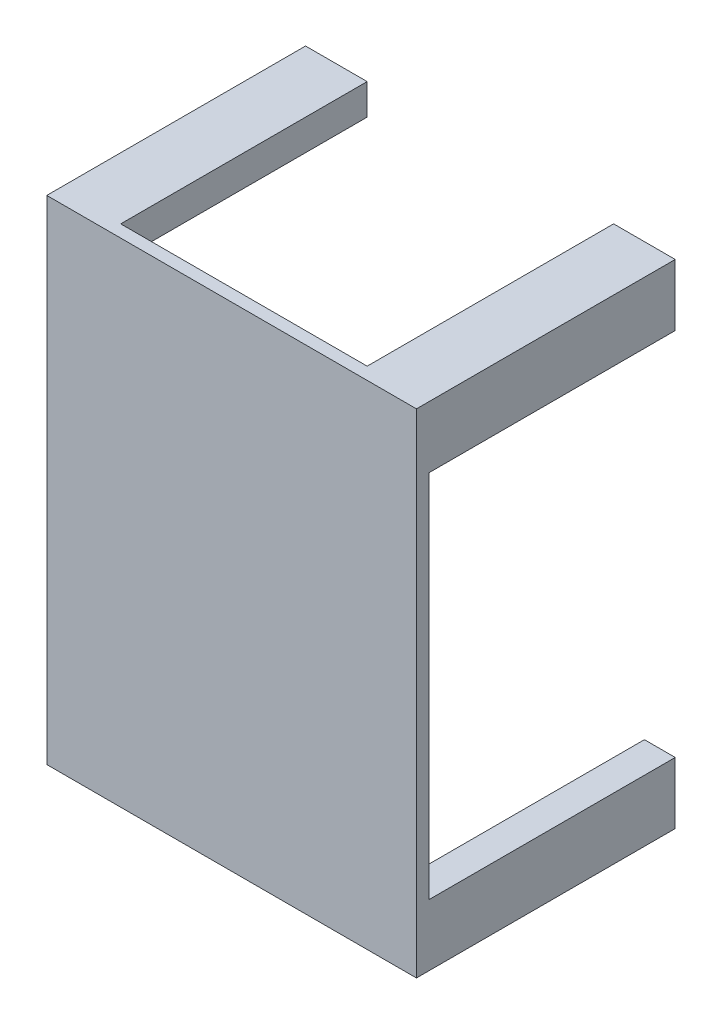
SolidWorks part; units mm, degrees
ref_plane "Plan de face" through (0, 0, 0) normal (0, 0, 1) x (1, 0, 0)
ref_plane "Plan de dessus" through (0, 0, 0) normal (0, 1, 0) x (1, 0, 0)
ref_plane "Plan de droite" through (0, 0, 0) normal (1, 0, 0) x (0, 0, -1)
sketch "Esquisse2" plane through (0, 0, 0) normal (0, 0, 1) x (1, 0, 0)
  line L0 (0, 0) -> (60, 0)
  line L1 (60, 0) -> (60, 80)
  line L2 (60, 80) -> (0, 80)
  line L3 (0, 80) -> (0, 0)
  dimension "D1" = 80
  dimension "D2" = 60
extrude "Boss.-Extru.1" add sketch "Esquisse2" along normal blind 2
sketch "Esquisse3" plane through (0, 0, 0) normal (0, 0, -1) x (-1, 0, 0)
  line L0 (0, 0) -> (-60, 0) construction
  line L1 (-60, 0) -> (-50, 0)
  line L2 (-50, 0) -> (-50, 5)
  line L3 (-50, 5) -> (-55, 5)
  line L4 (-55, 5) -> (-55, 10)
  line L5 (-55, 10) -> (-60, 10)
  line L6 (-60, 0) -> (-60, 80) construction
  line L7 (-60, 10) -> (-60, 0)
  line L8 (0, 0) -> (-10, 0)
  line L9 (-10, 0) -> (-10, 5)
  line L10 (-10, 5) -> (-5, 5)
  line L11 (-5, 5) -> (-5, 10)
  line L12 (-5, 10) -> (0, 10)
  line L13 (0, 80) -> (0, 0) construction
  line L14 (0, 10) -> (0, 0)
  line L15 (0, 80) -> (-10, 80)
  line L16 (-60, 80) -> (0, 80) construction
  line L17 (-10, 80) -> (-10, 75)
  line L18 (-10, 75) -> (-5, 75)
  line L19 (-5, 75) -> (-5, 70)
  line L20 (-5, 70) -> (0, 70)
  line L21 (0, 70) -> (0, 80)
  line L22 (-60, 80) -> (-50, 80)
  line L23 (-50, 80) -> (-50, 75)
  line L24 (-50, 75) -> (-55, 75)
  line L25 (-55, 75) -> (-55, 70)
  line L26 (-55, 70) -> (-60, 70)
  line L27 (-60, 70) -> (-60, 80)
  dimension "D1" = 10
  dimension "D2" = 10
  dimension "D3" = 5
  dimension "D4" = 5
  dimension "D5" = 10
  dimension "D6" = 5
  dimension "D7" = 5
  dimension "D8" = 5
  dimension "D9" = 5
  dimension "D10" = 5
  dimension "D11" = 5
  dimension "D12" = 10
  dimension "D13" = 5
  dimension "D14" = 10
extrude "Boss.-Extru.3" add sketch "Esquisse3" along normal blind 40 contours L27 L22 L23 L24 L25 L26 | L21 L15 L17 L18 L19 L20 | L14 L8 L9 L10 L11 L12 | L7 L1 L2 L3 L4 L5
